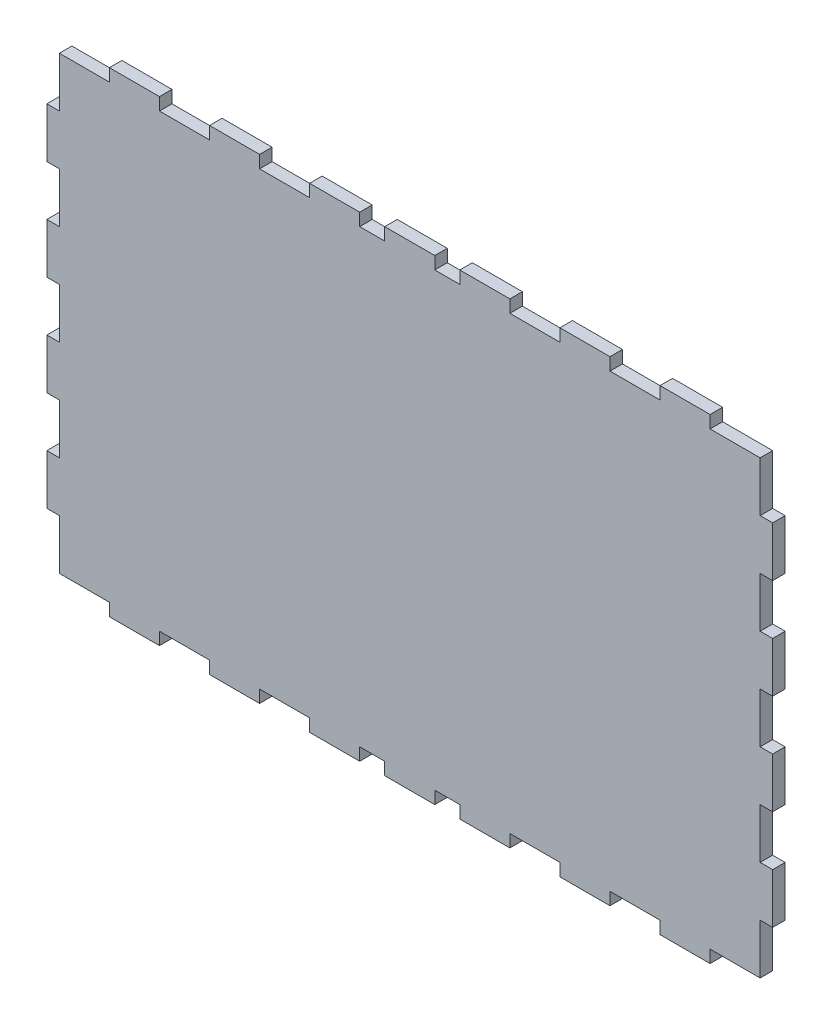
SolidWorks part; units mm, degrees
ref_plane "Front Plane" through (0, 0, 0) normal (0, 0, 1) x (1, 0, 0)
ref_plane "Top Plane" through (0, 0, 0) normal (0, 1, 0) x (1, 0, 0)
ref_plane "Right Plane" through (0, 0, 0) normal (1, 0, 0) x (0, 0, -1)
sketch "Sketch1" plane through (0, 0, 0) normal (0, 0, 1) x (1, 0, 0)
  line L0 (164.2656, 19.2892) -> (164.2656, 25.6392)
  line L1 (164.2656, 25.6392) -> (189.6656, 25.6392)
  line L2 (189.6656, 25.6392) -> (189.6656, 19.2892)
  line L3 (189.6656, 19.2892) -> (215.0656, 19.2892)
  line L4 (215.0656, 19.2892) -> (215.0656, 25.6392)
  line L5 (215.0656, 25.6392) -> (240.4656, 25.6392)
  line L6 (240.4656, 25.6392) -> (240.4656, 19.2892)
  line L7 (240.4656, 19.2892) -> (265.8656, 19.2892)
  line L8 (265.8656, 19.2892) -> (265.8656, 25.6392)
  line L9 (265.8656, 25.6392) -> (291.2656, 25.6392)
  line L10 (291.2656, 25.6392) -> (291.2656, 19.2892)
  line L11 (469.0656, 19.2892) -> (469.0656, 25.6392)
  line L12 (469.0656, 25.6392) -> (443.6656, 25.6392)
  line L13 (443.6656, 25.6392) -> (443.6656, 19.2892)
  line L14 (443.6656, 19.2892) -> (418.2656, 19.2892)
  line L15 (418.2656, 19.2892) -> (418.2656, 25.6392)
  line L16 (418.2656, 25.6392) -> (392.8656, 25.6392)
  line L17 (392.8656, 25.6392) -> (392.8656, 19.2892)
  line L18 (392.8656, 19.2892) -> (367.4656, 19.2892)
  line L19 (367.4656, 19.2892) -> (367.4656, 25.6392)
  line L20 (367.4656, 25.6392) -> (342.0656, 25.6392)
  line L21 (342.0656, 25.6392) -> (342.0656, 19.2892)
  line L22 (291.2656, 19.2892) -> (303.9656, 19.2892)
  line L23 (303.9656, 19.2892) -> (303.9656, 25.6392)
  line L24 (303.9656, 25.6392) -> (329.3656, 25.6392)
  line L25 (329.3656, 25.6392) -> (329.3656, 19.2892)
  line L26 (329.3656, 19.2892) -> (342.0656, 19.2892)
  line L27 (164.2656, -209.3108) -> (164.2656, -215.6608)
  line L28 (164.2656, -215.6608) -> (189.6656, -215.6608)
  line L29 (189.6656, -215.6608) -> (189.6656, -209.3108)
  line L30 (189.6656, -209.3108) -> (215.0656, -209.3108)
  line L31 (215.0656, -209.3108) -> (215.0656, -215.6608)
  line L32 (215.0656, -215.6608) -> (240.4656, -215.6608)
  line L33 (240.4656, -215.6608) -> (240.4656, -209.3108)
  line L34 (240.4656, -209.3108) -> (265.8656, -209.3108)
  line L35 (265.8656, -209.3108) -> (265.8656, -215.6608)
  line L36 (265.8656, -215.6608) -> (291.2656, -215.6608)
  line L37 (291.2656, -215.6608) -> (291.2656, -209.3108)
  line L38 (469.0656, -209.3108) -> (469.0656, -215.6608)
  line L39 (469.0656, -215.6608) -> (443.6656, -215.6608)
  line L40 (443.6656, -215.6608) -> (443.6656, -209.3108)
  line L41 (443.6656, -209.3108) -> (418.2656, -209.3108)
  line L42 (418.2656, -209.3108) -> (418.2656, -215.6608)
  line L43 (418.2656, -215.6608) -> (392.8656, -215.6608)
  line L44 (392.8656, -215.6608) -> (392.8656, -209.3108)
  line L45 (392.8656, -209.3108) -> (367.4656, -209.3108)
  line L46 (367.4656, -209.3108) -> (367.4656, -215.6608)
  line L47 (367.4656, -215.6608) -> (342.0656, -215.6608)
  line L48 (342.0656, -215.6608) -> (342.0656, -209.3108)
  line L49 (291.2656, -209.3108) -> (303.9656, -209.3108)
  line L50 (303.9656, -209.3108) -> (303.9656, -215.6608)
  line L51 (303.9656, -215.6608) -> (329.3656, -215.6608)
  line L52 (329.3656, -215.6608) -> (329.3656, -209.3108)
  line L53 (329.3656, -209.3108) -> (342.0656, -209.3108)
  line L54 (138.8656, -6.1108) -> (132.5156, -6.1108)
  line L55 (132.5156, -6.1108) -> (132.5156, -31.5108)
  line L56 (132.5156, -31.5108) -> (138.8656, -31.5108)
  line L57 (138.8656, -31.5108) -> (138.8656, -56.9108)
  line L58 (138.8656, -56.9108) -> (132.5156, -56.9108)
  line L59 (132.5156, -56.9108) -> (132.5156, -82.3108)
  line L60 (132.5156, -82.3108) -> (138.8656, -82.3108)
  line L61 (138.8656, -82.3108) -> (138.8656, -107.7108)
  line L62 (138.8656, -107.7108) -> (132.5156, -107.7108)
  line L63 (132.5156, -107.7108) -> (132.5156, -133.1108)
  line L64 (132.5156, -133.1108) -> (138.8656, -133.1108)
  line L65 (138.8656, -133.1108) -> (138.8656, -158.5108)
  line L66 (138.8656, -158.5108) -> (132.5156, -158.5108)
  line L67 (132.5156, -158.5108) -> (132.5156, -183.9108)
  line L68 (132.5156, -183.9108) -> (138.8656, -183.9108)
  line L69 (138.8656, -183.9108) -> (138.8656, -209.3108)
  line L70 (138.8656, -6.1108) -> (138.8656, 19.2892)
  line L71 (164.2656, 19.2892) -> (138.8656, 19.2892)
  line L72 (164.2656, -209.3108) -> (138.8656, -209.3108)
  line L73 (494.4656, -6.1108) -> (500.8156, -6.1108)
  line L74 (500.8156, -6.1108) -> (500.8156, -31.5108)
  line L75 (500.8156, -31.5108) -> (494.4656, -31.5108)
  line L76 (494.4656, -31.5108) -> (494.4656, -56.9108)
  line L77 (494.4656, -56.9108) -> (500.8156, -56.9108)
  line L78 (500.8156, -56.9108) -> (500.8156, -82.3108)
  line L79 (500.8156, -82.3108) -> (494.4656, -82.3108)
  line L80 (494.4656, -82.3108) -> (494.4656, -107.7108)
  line L81 (494.4656, -107.7108) -> (500.8156, -107.7108)
  line L82 (500.8156, -107.7108) -> (500.8156, -133.1108)
  line L83 (500.8156, -133.1108) -> (494.4656, -133.1108)
  line L84 (494.4656, -133.1108) -> (494.4656, -158.5108)
  line L85 (494.4656, -158.5108) -> (500.8156, -158.5108)
  line L86 (500.8156, -158.5108) -> (500.8156, -183.9108)
  line L87 (500.8156, -183.9108) -> (494.4656, -183.9108)
  line L88 (494.4656, -183.9108) -> (494.4656, -209.3108)
  line L89 (494.4656, -6.1108) -> (494.4656, 19.2892)
  line L90 (469.0656, 19.2892) -> (494.4656, 19.2892)
  line L91 (469.0656, -209.3108) -> (494.4656, -209.3108)
extrude "Extrude1" add sketch "Sketch1" along normal blind 6.35
